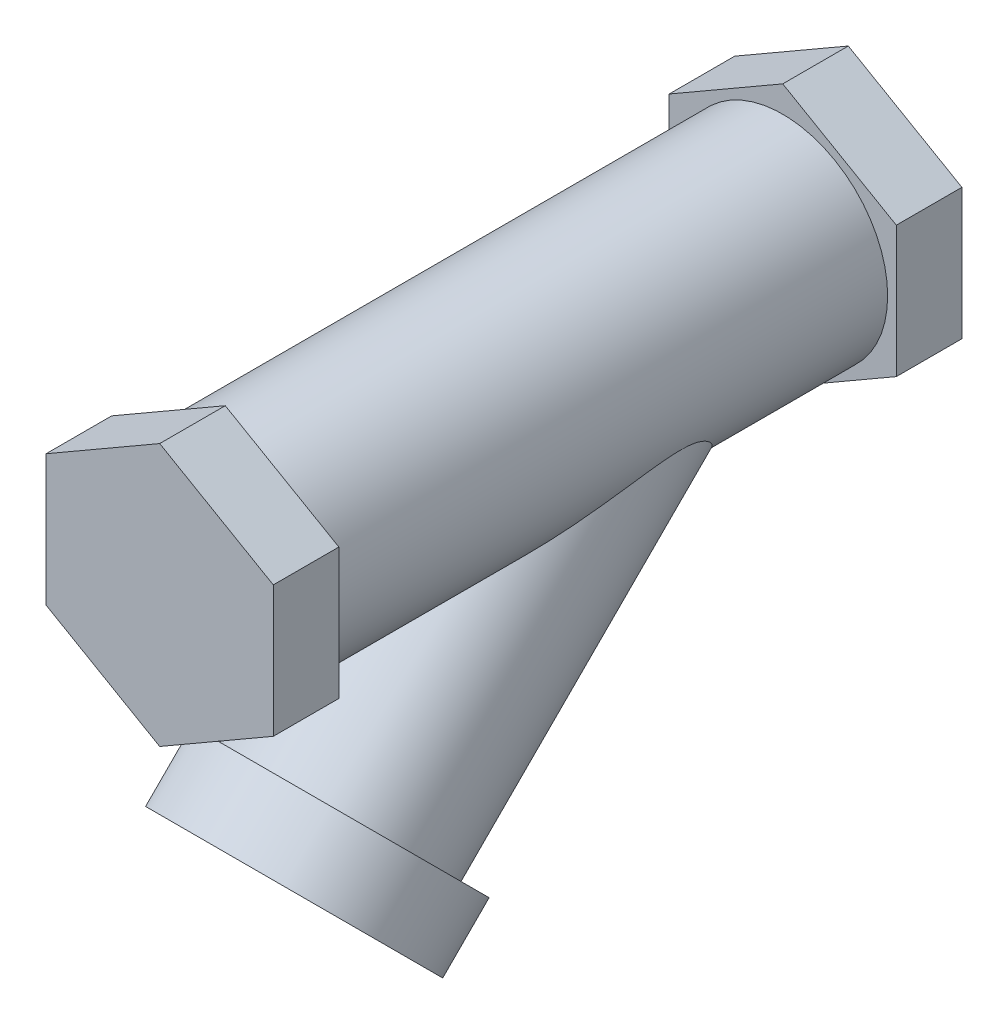
SolidWorks part; units mm, degrees
material "Простая углеродистая сталь"
ref_plane "Плоскость1" through (0, 0, 0) normal (0, 0, 1) x (1, 0, 0)
ref_plane "Плоскость2" through (0, 0, 0) normal (0, 1, 0) x (1, 0, 0)
ref_plane "Плоскость3" through (0, 0, 0) normal (1, 0, 0) x (0, 0, -1)
sketch "Эскиз1" plane through (0, 0, 0) normal (0, 0, 1) x (1, 0, 0)
  line L0 (0, 80) -> (0, -110) construction
  line L1 (-100, 0) -> (160, 0) construction
sketch "Эскиз2" plane through (0, 0, 0) normal (1, 0, 0) x (0, 0, -1)
  line L0 (-450, 0) -> (400, 0) construction
  line L1 (0, 0) -> (-170, -170) construction
  dimension "D1" = 45
sketch "Эскиз3" plane through (0, 0, 0) normal (0, 0, 1) x (1, 0, 0)
  circle A1 centre (0, 0) radius 16
  dimension "D2" = 32
extrude "Основание-Вытянуть" add sketch "Эскиз3" along normal blind 60
ref_plane "Плоскость4" through (0, 0, 0) normal (0, -0.7071, 0.7071) x (1, 0, 0)
sketch "Эскиз4" plane through (0, 0, 0) normal (0, -0.7071, 0.7071) x (1, 0, 0)
  circle A0 centre (0, 0) radius 15
  dimension "D1" = 30
extrude "Бобышка-Вытянуть1" add sketch "Эскиз4" along normal blind 60
sketch "Эскиз8" plane through (0, -42.4264, 42.4264) normal (0, -0.7071, 0.7071) x (1, 0, 0)
  circle A1 centre (0, 0) radius 15
  circle A2 centre (0, 0) radius 15
  dimension "D1" = 0
sketch "Эскиз9" plane through (0, -42.4264, 42.4264) normal (0, -0.7071, 0.7071) x (1, 0, 0)
  circle A0 centre (0, 0) radius 18.5
  dimension "D1" = 37
extrude "Бобышка-Вытянуть2" add sketch "Эскиз9" along normal blind 10
sketch "Эскиз12" plane through (0, 0, 60) normal (0, 0, 1) x (1, 0, 0)
  line L1 (0, 20) -> (-17.3205, 10)
  line L2 (-17.3205, 10) -> (-17.3205, -10)
  line L3 (-17.3205, -10) -> (0, -20)
  line L4 (0, -20) -> (17.3205, -10)
  line L5 (17.3205, -10) -> (17.3205, 10)
  line L6 (17.3205, 10) -> (0, 20)
  circle A0 centre (0, 0) radius 17.3205 construction
  dimension "D1" = 40
extrude "Бобышка-Вытянуть5" add sketch "Эскиз12" along normal blind 10
sketch "Эскиз13" plane through (0, 0, 0) normal (0, 0, -1) x (-1, 0, 0)
  circle A0 centre (0, 0) radius 16
  circle A1 centre (0, 0) radius 16 construction
extrude "Бобышка-Вытянуть6" add sketch "Эскиз13" along normal blind 25
sketch "Эскиз14" plane through (0, 0, -25) normal (0, 0, -1) x (-1, 0, 0)
  line L0 (17.3205, -10) -> (0, -20) construction
  line L1 (0, -20) -> (17.3205, -10)
  line L2 (17.3205, -10) -> (17.3205, 10)
  line L3 (17.3205, 10) -> (0, 20)
  line L4 (0, 20) -> (-17.3205, 10)
  line L5 (-17.3205, 10) -> (-17.3205, -10)
  line L6 (-17.3205, -10) -> (0, -20)
  circle A0 centre (0, 0) radius 17.3205 construction
extrude "Бобышка-Вытянуть7" add sketch "Эскиз14" along normal blind 10
